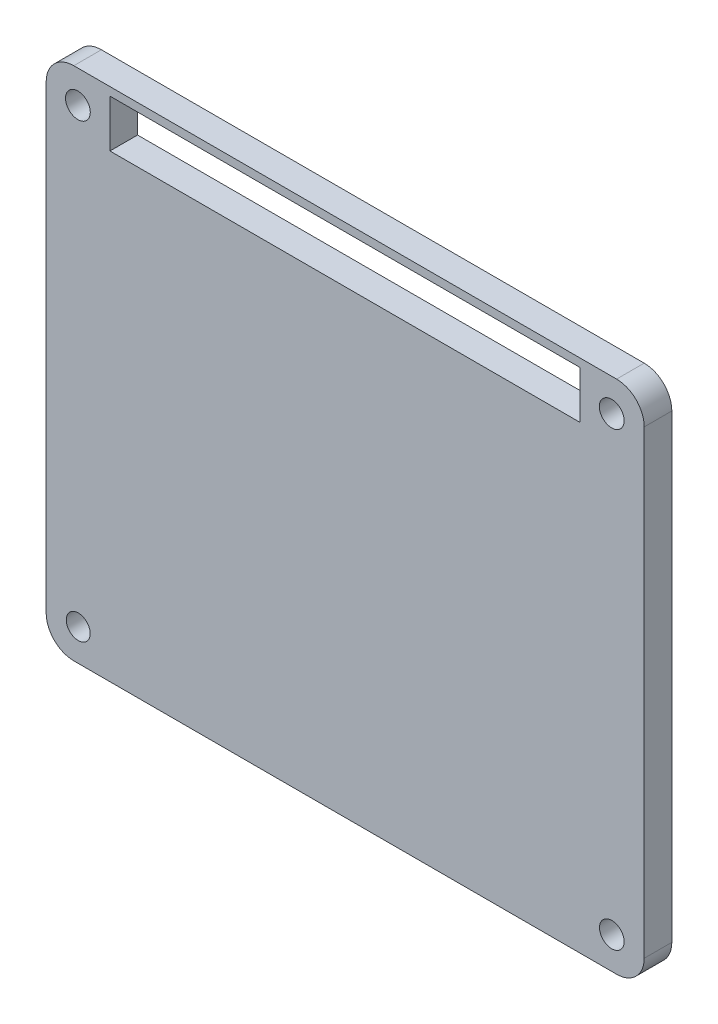
SolidWorks part; units mm, degrees
material "Verre"
ref_plane "Plan de face" through (0, 0, 0) normal (0, 0, 1) x (1, 0, 0)
ref_plane "Plan de dessus" through (0, 0, 0) normal (0, 1, 0) x (1, 0, 0)
ref_plane "Plan de droite" through (0, 0, 0) normal (1, 0, 0) x (0, 0, -1)
sketch "Esquisse1" plane through (0, 0, 0) normal (0, 0, 1) x (1, 0, 0)
  line L0 (139.887, 293.2101) -> (204.887, 293.2101) construction
  line L1 (142.9143, 306.3335) -> (201.8719, 306.3335)
  line L2 (204.8719, 303.3335) -> (204.8719, 253.3481)
  line L3 (201.8719, 250.3481) -> (142.9143, 250.3481)
  line L4 (139.9143, 253.3481) -> (139.9143, 303.3335)
  line L6 (146.8413, 305.4381) -> (197.9018, 305.4381)
  line L7 (146.8413, 305.4381) -> (146.8413, 300.2753)
  line L8 (146.8413, 300.2753) -> (197.9018, 300.2753)
  line L9 (197.9018, 305.4381) -> (197.9018, 300.2753)
  arc A0 (204.8719, 253.3481) -> (201.8719, 250.3481) centre (201.8719, 253.3481) cw
  arc A1 (201.8719, 306.3335) -> (204.8719, 303.3335) centre (201.8719, 303.3335) cw
  arc A2 (142.9143, 250.3481) -> (139.9143, 253.3481) centre (142.9143, 253.3481) cw
  arc A3 (142.9143, 306.3335) -> (139.9143, 303.3335) centre (142.9143, 303.3335) ccw
  circle A4 centre (143.3605, 302.8316) radius 1.3453
  circle A5 centre (201.3447, 302.8186) radius 1.3469
  circle A6 centre (143.3955, 253.802) radius 1.2986
  circle A7 centre (201.3549, 253.8151) radius 1.3357
  dimension "D2" = 3
  dimension "D1" = 65
extrude "Boss.-Extru.1" add sketch "Esquisse1" along normal blind 3
